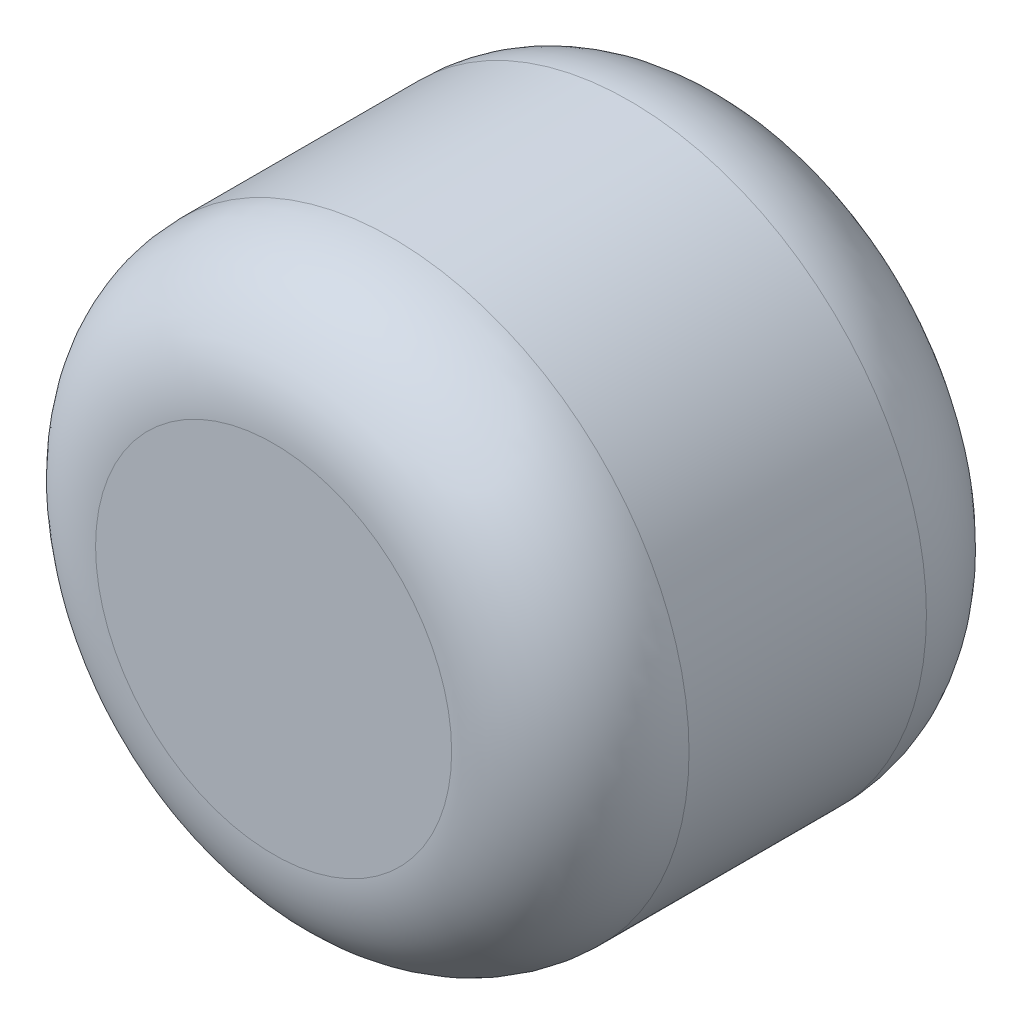
SolidWorks part; units mm, degrees
ref_plane "Plan de face" through (0, 0, 0) normal (0, 0, 1) x (1, 0, 0)
ref_plane "Plan de dessus" through (0, 0, 0) normal (0, 1, 0) x (1, 0, 0)
ref_plane "Plan de droite" through (0, 0, 0) normal (1, 0, 0) x (0, 0, -1)
sketch "Esquisse1" plane through (0, 0, 0) normal (0, 0, 1) x (1, 0, 0)
  circle A0 centre (0, 0) radius 63.5
  dimension "D1" = 127
extrude "Boss.-Extru.1" add sketch "Esquisse1" along normal blind 101.6
fillet "Congé1" radius 25.4 2 edges at (63.5, 0, 0) (63.5, 0, 101.6)
